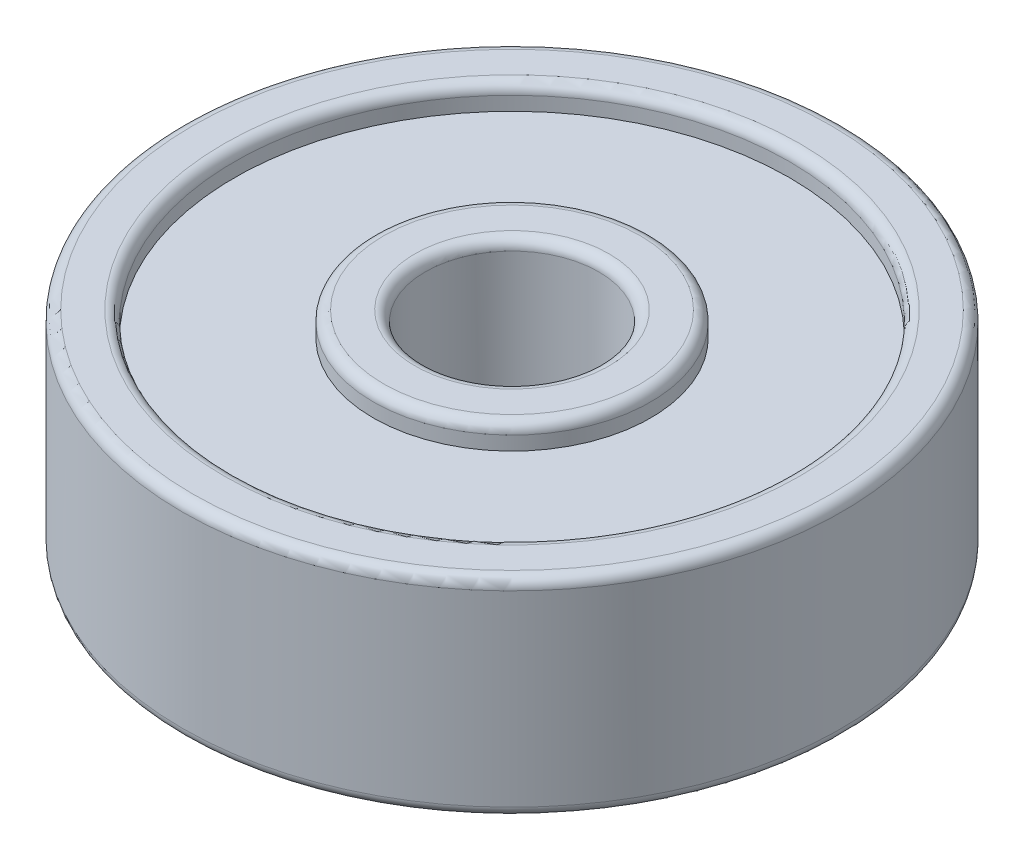
SolidWorks part; units mm, degrees
ref_plane "前视基准面" through (0, 0, 0) normal (0, 0, 1) x (1, 0, 0)
ref_plane "上视基准面" through (0, 0, 0) normal (0, 1, 0) x (1, 0, 0)
ref_plane "右视基准面" through (0, 0, 0) normal (1, 0, 0) x (0, 0, -1)
other "Configuration Table"
sketch "草图1" plane through (0, 0, 0) normal (0, 0, 1) x (1, 0, 0)
  line L0 (0, 4.6113) -> (0, -3.0029) construction
  line L1 (2.5, 6) -> (2.5, 0)
  line L2 (2.5, 0) -> (4, 0)
  line L3 (4, 0) -> (4, 0.7)
  line L4 (4, 0.7) -> (8, 0.7)
  line L5 (8, 0.7) -> (8, 0)
  line L6 (8, 0) -> (9.5, 0)
  line L7 (9.5, 0) -> (9.5, 6)
  line L8 (9.5, 6) -> (8, 6)
  line L9 (8, 6) -> (8, 5.3)
  line L10 (8, 5.3) -> (4, 5.3)
  line L11 (4, 5.3) -> (4, 6)
  line L12 (4, 6) -> (2.5, 6)
  dimension "D1" = 2.5
  dimension "D2" = 9.5
  dimension "D3" = 6
  dimension "D4" = 1.5
  dimension "D5" = 1.5
  dimension "D6" = 0.7
  dimension "D7" = 0.7
revolve "旋转1" add sketch "草图1" angle 360 about L0
fillet "圆角1" radius 0.3 8 edges at (0, 0, 2.5) (0, 0, 4) (0, 0, 8) (0, 0, 9.5) (0, 6, 4) (0, 6, 2.5) (0, 6, 9.5) (0, 6, 8)
